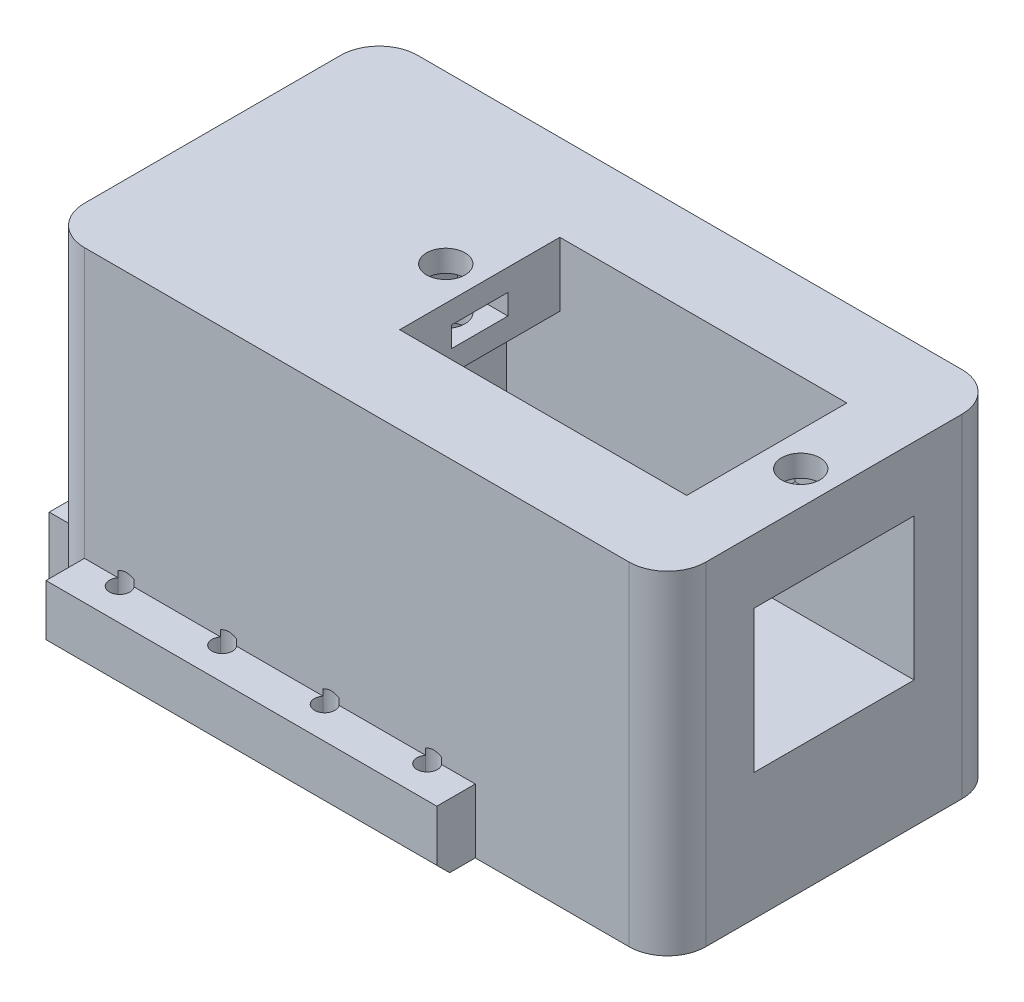
SolidWorks part; units mm, degrees
ref_plane "Front" through (0, 0, 0) normal (0, 0, 1) x (1, 0, 0)
ref_plane "Top" through (0, 0, 0) normal (0, 1, 0) x (1, 0, 0)
ref_plane "Right" through (0, 0, 0) normal (1, 0, 0) x (0, 0, -1)
sketch "草图1" plane through (0, 0, 0) normal (0, 1, 0) x (1, 0, 0)
  line L1 (-24.25, 13) -> (24.25, 13)
  line L2 (-24.25, 13) -> (-24.25, -13)
  line L3 (-24.25, -13) -> (24.25, -13)
  line L4 (24.25, 13) -> (24.25, -13)
  line L5 (-24.25, 13) -> (24.25, -13) construction
  line L6 (-24.25, -13) -> (24.25, 13) construction
  point P0 (0, 0)
  dimension "D1" = 48.5
  dimension "D2" = 26
extrude "凸台-拉伸1" add sketch "草图1" along normal blind 26
sketch "草图16" plane through (0, 26, 0) normal (0, 1, 0) x (1, 0, 0)
  line L0 (24.25, -13) -> (24.25, 13) construction
  line L1 (-3.4, -6.25) -> (19, -6.25)
  line L2 (-3.4, -6.25) -> (-3.4, 6.25)
  line L3 (-3.4, 6.25) -> (19, 6.25)
  line L4 (19, -6.25) -> (19, 6.25)
  line L5 (-3.4, -6.25) -> (19, 6.25) construction
  line L6 (-3.4, 6.25) -> (19, -6.25) construction
  point P0 (7.8, 0)
  dimension "D1" = 5.25
  dimension "D2" = 22.4
  dimension "D3" = 12.5
extrude "切除-拉伸13" cut sketch "草图16" against normal blind 16.1
sketch "草图17" plane through (24.25, 0, 0) normal (1, 0, 0) x (0, 0, -1)
  line L0 (-6.25, 21) -> (6.25, 21)
  line L4 (6.25, 26) -> (-6.25, 26)
  line L5 (6.25, 9.9) -> (6.25, 26)
  line L6 (-6.25, 9.9) -> (6.25, 9.9)
  line L7 (-6.25, 26) -> (-6.25, 9.9)
  line L9 (6.25, 9.9) -> (6.25, 21)
  line L10 (-6.25, 9.9) -> (6.25, 9.9)
  line L11 (-6.25, 21) -> (-6.25, 9.9)
  dimension "D1" = 0
extrude "切除-拉伸14" cut sketch "草图17" against normal blind 31.8
ref_plane "基准面1" through (0, 23.5, 0) normal (0, 1, 0) x (1, 0, 0)
sketch "草图18" plane through (0, 26, 0) normal (0, 1, 0) x (1, 0, 0)
  line L0 (7.8, 6.25) -> (7.8, -6.25) construction
  line L3 (19, 6.25) -> (-3.4, 6.25) construction
  line L6 (-3.4, -6.25) -> (19, -6.25) construction
  line L7 (24.25, 0) -> (-24.25, 0) construction
  line L8 (24.25, -13) -> (24.25, 13) construction
  line L9 (-24.25, 13) -> (-24.25, -13) construction
  circle A0 centre (21.65, 0) radius 1.5
  circle A1 centre (-6.05, 0) radius 1.5
  dimension "D1" = 27.7
extrude "切除-拉伸15" cut sketch "草图18" against normal up to next
sketch "草图20" plane through (0, 0, 0) normal (0, -1, 0) x (1, 0, 0)
  line L0 (-19.75, -3) -> (-12.75, -3)
  line L1 (-12.75, 10) -> (-19.75, 10)
  line L2 (24.25, 13) -> (24.25, -13) construction
  line L3 (-12.75, -10) -> (-19.75, -10)
  line L4 (-19.75, 10) -> (-19.75, 3)
  line L7 (-12.75, -3) -> (-12.75, -10)
  line L8 (-19.75, 3) -> (-12.75, 3)
  line L9 (-12.75, 3) -> (-12.75, 10)
  line L10 (-19.75, -3) -> (-19.75, -10)
  point P0 (0, 0)
  point P6 (-19.75, 3)
  point P7 (-19.75, -3)
  point P8 (-19.75, 3)
  dimension "D1" = 7
  dimension "D2" = 20
  dimension "D3" = 7
  dimension "D4" = 7
  dimension "D5" = 7
  dimension "D6" = 44
extrude "凸台-拉伸2" add sketch "草图20" along normal blind 3
sketch "草图21" plane through (0, 0, -10) normal (0, 0, -1) x (-1, 0, 0)
  line L1 (12.75, 0) -> (16.5, -3)
  line L2 (16.5, -3) -> (12.75, -3)
  line L3 (12.75, 0) -> (12.75, -3)
  line L5 (19.75, -3) -> (12.75, -3) construction
extrude "切除-拉伸16" cut sketch "草图21" against normal through all
fillet "圆角4" radius 2 2 edges at (-16.5, -3, -6.5) (-16.5, -3, 6.5)
sketch "草图23" plane through (0, 0, 0) normal (0, -1, 0) x (1, 0, 0)
  line L0 (-24.25, 0) -> (24.25, 0) construction
  line L1 (-24.25, -13) -> (-24.25, 13) construction
  line L2 (24.25, 13) -> (24.25, -13) construction
  circle A0 centre (12.75, 0) radius 4
  dimension "D1" = 8
  dimension "D2" = 11.5
sketch "草图27" plane through (0, 23.5, 0) normal (0, 1, 0) x (1, 0, 0)
  line L0 (7.8, 6.25) -> (7.8, -6.25) construction
  line L1 (-3.4, 2.2) -> (-3.4, -2.2)
  line L2 (19, 2.2) -> (19, -2.2)
  line L5 (20.4953, 2.2) -> (22.9202, 2.2)
  line L6 (22.9202, 2.2) -> (24.1903, 0)
  line L7 (19, 6.25) -> (-3.4, 6.25) construction
  line L8 (-7.55, -6.25) -> (24.25, -6.25) construction
  line L9 (24.1903, 0) -> (22.9202, -2.2)
  line L10 (22.9202, -2.2) -> (20.4953, -2.2)
  line L12 (19, -2.2) -> (20.4953, -2.2)
  line L13 (20.4953, 2.2) -> (19, 2.2)
  line L21 (-4.8953, 2.2) -> (-3.4, 2.2)
  line L23 (-3.4, -2.2) -> (-4.8953, -2.2)
  line L24 (-7.3202, -2.2) -> (-4.8953, -2.2)
  line L25 (-8.5903, 0) -> (-7.3202, -2.2)
  line L26 (-7.3202, 2.2) -> (-8.5903, 0)
  line L27 (-4.8953, 2.2) -> (-7.3202, 2.2)
extrude "切除-拉伸19" cut sketch "草图27" along normal mid plane 1.6
fillet "圆角6" radius 3 4 edges at (24.25, 13, 13) (24.25, 13, -13) (-24.25, 13, -13) (-24.25, 13, 13)
sketch "草图28" plane through (0, 0, 0) normal (0, -1, 0) x (1, 0, 0)
  line L0 (-24.25, -10) -> (-24.25, 10) construction
  line L1 (-21.25, 13) -> (9.25, 13)
  line L2 (-21.25, 13) -> (-21.25, 16)
  line L3 (-21.25, 16) -> (9.25, 16)
  line L4 (9.25, 13) -> (9.25, 16)
  line L5 (-24.25, 4.75) -> (-25.75, 4.75)
  line L6 (-24.25, -10) -> (-24.25, -4.75)
  line L7 (-23.9772, 11.25) -> (-25.75, 11.25)
  line L8 (-25.75, 4.75) -> (-25.75, 11.25)
  line L9 (-21.25, -13) -> (9.25, -13)
  line L10 (-21.25, -13) -> (-21.25, -16)
  line L11 (-21.25, -16) -> (9.25, -16)
  line L12 (9.25, -13) -> (9.25, -16)
  line L13 (-25.75, -8) -> (-24.25, -8) construction
  line L14 (-24.25, -4.75) -> (-25.75, -4.75)
  line L15 (-24.25, 4.75) -> (-24.25, 10)
  line L16 (-23.9772, -11.25) -> (-25.75, -11.25)
  line L17 (-25.75, -4.75) -> (-25.75, -11.25)
  line L18 (-25.75, 8) -> (-24.25, 8) construction
  line L19 (-17.2016, 10) -> (-19.75, 10) construction
  line L20 (-19.75, -10) -> (-12.75, -10) construction
  arc A0 (-21.25, 13) -> (-24.25, 10) centre (-21.25, 10) ccw construction
  arc A1 (-24.25, -10) -> (-21.25, -13) centre (-21.25, -10) ccw construction
  arc A2 (-23.9772, 11.25) -> (-24.25, 10) centre (-21.25, 10) ccw
  arc A3 (-24.25, -10) -> (-23.9772, -11.25) centre (-21.25, -10) ccw
  dimension "D1" = 30.5
  dimension "D2" = 3
  dimension "D3" = 30.5
  dimension "D4" = 3
  dimension "D5" = 1.5
  dimension "D6" = 1.5
  dimension "D7" = 6.5
  dimension "D8" = 6.5
  dimension "D9" = 2
  dimension "D10" = 2
extrude "凸台-拉伸4" add sketch "草图28" against normal blind 5 separate body
sketch "草图31" plane through (0, 0, 0) normal (0, -1, 0) x (1, 0, 0)
  line L0 (-19.75, -3) -> (-19.75, -10) construction
  line L1 (-19.75, -10) -> (-17.2016, -10) construction
  line L3 (-19.75, 10) -> (-19.75, 3) construction
  line L5 (-24.25, 0) -> (24.25, 0) construction
  line L6 (-24.25, -10) -> (-24.25, 10) construction
  line L7 (24.25, 10) -> (24.25, -10) construction
  line L9 (-21.25, -13) -> (-21.25, -16) construction
  point P0 (-18, -13.5)
  point P1 (-10, 13.5)
  point P3 (-10, -13.5)
  point P8 (-23.25, -8.175)
  point P9 (-23.25, 8.175)
  point P22 (-2, 13.5)
  point P23 (6, 13.5)
  point P25 (-18, 13.5)
  point P26 (-2, -13.5)
  point P27 (6, -13.5)
  dimension "D1" = 3.25
  dimension "D2" = 4
  dimension "D3" = 4
  dimension "D4" = 16.35
  dimension "D5" = 3.5
  dimension "D6" = 8.175
  dimension "D7" = 3.5
  dimension "D9" = 3.5
hole_wizard "M2x0.4 螺纹孔1" positions "3D草图1" profile "草图32" tap size "M2x0.4" standard "ANSI Metric"
sketch3d "3D草图1"
  point P0 (-18, 0, -13.5)
  point P3 (-10, 0, -13.5)
  point P6 (-2, 0, -13.5)
  point P9 (6, 0, -13.5)
  point P12 (-23.25, 0, -8.175)
  point P15 (-23.25, 0, 8.175)
  point P18 (-18, 0, 13.5)
  point P21 (-10, 0, 13.5)
  point P24 (-2, 0, 13.5)
  point P27 (6, 0, 13.5)
sketch "草图32" plane through (-18, 0, -13.5) normal (1, 0, 0) x (0, 0, -1)
  line L0 (0, 0) -> (0, 5.9807)
  line L1 (0, 5.9807) -> (0.8, 5.5)
  line L2 (0.8, 5.5) -> (0.8, 0)
  line L5 (0.8, 0) -> (0, 0)
  line L10 (0, 5.9807) -> (-0.8, 5.5) construction
  line L11 (0, -6.35) -> (0, 107.95) construction
  dimension "螺纹孔钻头直径" = 1.6
  dimension "螺纹孔钻头深度" = 5.5
  dimension "导头角度" = 118
cosmetic thread "孔螺蚊线1" parameters "D1"=2.4, "D2"=2
cosmetic thread "孔螺蚊线2" parameters "D1"=2.4, "D2"=2
cosmetic thread "孔螺蚊线3" parameters "D1"=2.4, "D2"=2
cosmetic thread "孔螺蚊线4" parameters "D1"=2.4, "D2"=2
cosmetic thread "孔螺蚊线7" parameters "D1"=2.4, "D2"=2
cosmetic thread "孔螺蚊线8" parameters "D1"=2.4, "D2"=2
cosmetic thread "孔螺蚊线9" parameters "D1"=2.4, "D2"=2
cosmetic thread "孔螺蚊线10" parameters "D1"=2.4, "D2"=2
cosmetic thread "孔螺蚊线11" parameters "D1"=2.4, "D2"=2
cosmetic thread "孔螺蚊线12" parameters "D1"=2.4, "D2"=2
chamfer "倒角1" distance 1 angle 45 1 edges at (-6, 0, 16)
chamfer "倒角2" distance 1 angle 45 1 edges at (-6, 0, -16)
extrude "切除-拉伸33" cut sketch "草图23" against normal blind 4
sketch "草图47" plane through (0, 4, 0) normal (0, -1, 0) x (1, 0, 0)
  line L1 (15.0594, 0) -> (13.9047, 2)
  line L2 (13.9047, 2) -> (11.5953, 2)
  line L3 (11.5953, 2) -> (10.4406, 0)
  line L4 (10.4406, 0) -> (11.5953, -2)
  line L5 (11.5953, -2) -> (13.9047, -2)
  line L6 (13.9047, -2) -> (15.0594, 0)
  circle A0 centre (12.75, 0) radius 2 construction
extrude "切除-拉伸34" cut sketch "草图47" against normal blind 1.6
